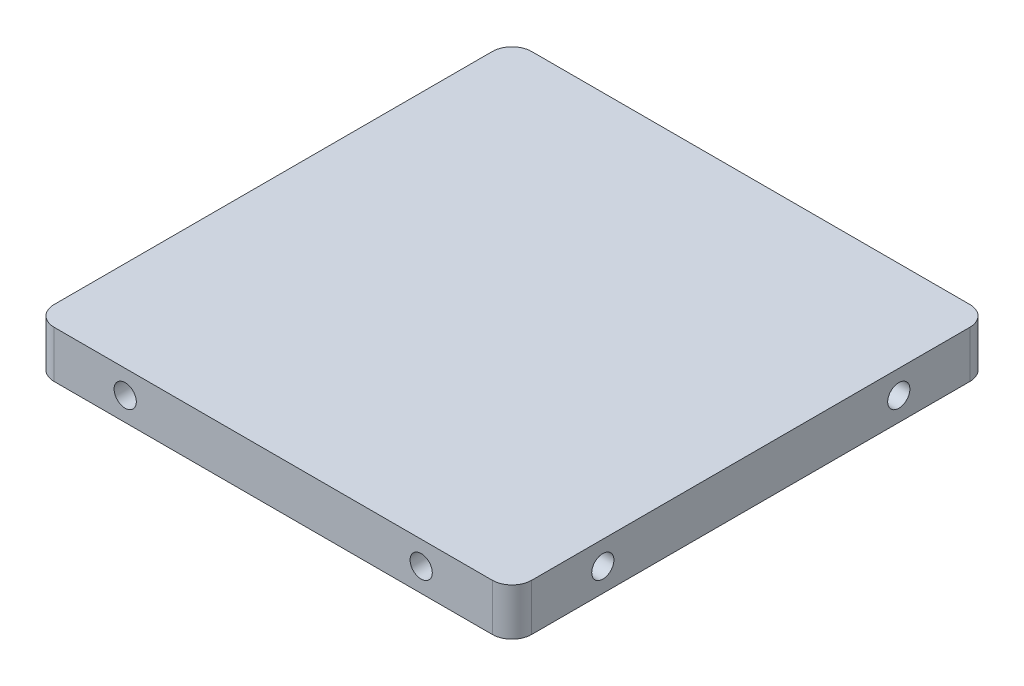
SolidWorks part; units mm, degrees
material "6061-T6 (SS)"
ref_plane "Front Plane" through (0, 0, 0) normal (0, 0, 1) x (1, 0, 0)
ref_plane "Top Plane" through (0, 0, 0) normal (0, 1, 0) x (1, 0, 0)
ref_plane "Right Plane" through (0, 0, 0) normal (1, 0, 0) x (0, 0, -1)
sketch "Sketch1" plane through (0, 0, 0) normal (0, 1, 0) x (1, 0, 0)
  line L1 (48.4125, -48.4125) -> (-48.4125, -48.4125)
  line L2 (48.4125, -48.4125) -> (48.4125, 48.4125)
  line L3 (48.4125, 48.4125) -> (-48.4125, 48.4125)
  line L4 (-48.4125, -48.4125) -> (-48.4125, 48.4125)
  line L5 (48.4125, -48.4125) -> (-48.4125, 48.4125) construction
  line L6 (48.4125, 48.4125) -> (-48.4125, -48.4125) construction
  point P0 (0, 0)
  dimension "D1" = 96.825
extrude "Boss-Extrude1" add sketch "Sketch1" along normal mid plane 9.525
fillet "Fillet1" radius 4 4 edges at (-48.4125, 0, -48.4125) (48.4125, 0, -48.4125) (48.4125, 0, 48.4125) (-48.4125, 0, 48.4125)
hole_wizard "M4 Clearance Hole1" positions "Sketch4" profile "Sketch3" hole size "M4" standard "ANSI Metric" end condition through all
sketch "Sketch4" plane through (-48.4125, 0, 0) normal (-1, 0, 0) x (0, 0, 1)
  point P0 (-30, 0)
  point P2 (30, 0)
  dimension "D1" = 30
  dimension "D2" = 30
sketch "Sketch3" plane through (-48.4125, 0, -30) normal (0, 1, 0) x (0, 0, 1)
  line L0 (0, 0) -> (0, 96.825)
  line L1 (0, 96.825) -> (2.25, 96.825)
  line L2 (2.25, 96.825) -> (2.25, 0)
  line L5 (2.25, 0) -> (0, 0)
  line L11 (0, -6.35) -> (0, 107.95) construction
  dimension "Thru Hole Dia." = 4.5
  dimension "Thru Hole Depth" = 96.825
hole_wizard "M4 Clearance Hole2" positions "Sketch7" profile "Sketch6" hole size "M4" standard "ANSI Metric" end condition through all
sketch "Sketch7" plane through (0, 0, -48.4125) normal (0, 0, -1) x (-1, 0, 0)
  point P0 (-30, 0)
  point P2 (30, 0)
  dimension "D1" = 30
  dimension "D2" = 30
sketch "Sketch6" plane through (30, 0, -48.4125) normal (1, 0, 0) x (0, 1, 0)
  line L0 (0, 0) -> (0, 96.825)
  line L1 (0, 96.825) -> (2.25, 96.825)
  line L2 (2.25, 96.825) -> (2.25, 0)
  line L5 (2.25, 0) -> (0, 0)
  line L11 (0, -6.35) -> (0, 107.95) construction
  dimension "Thru Hole Dia." = 4.5
  dimension "Thru Hole Depth" = 96.825
